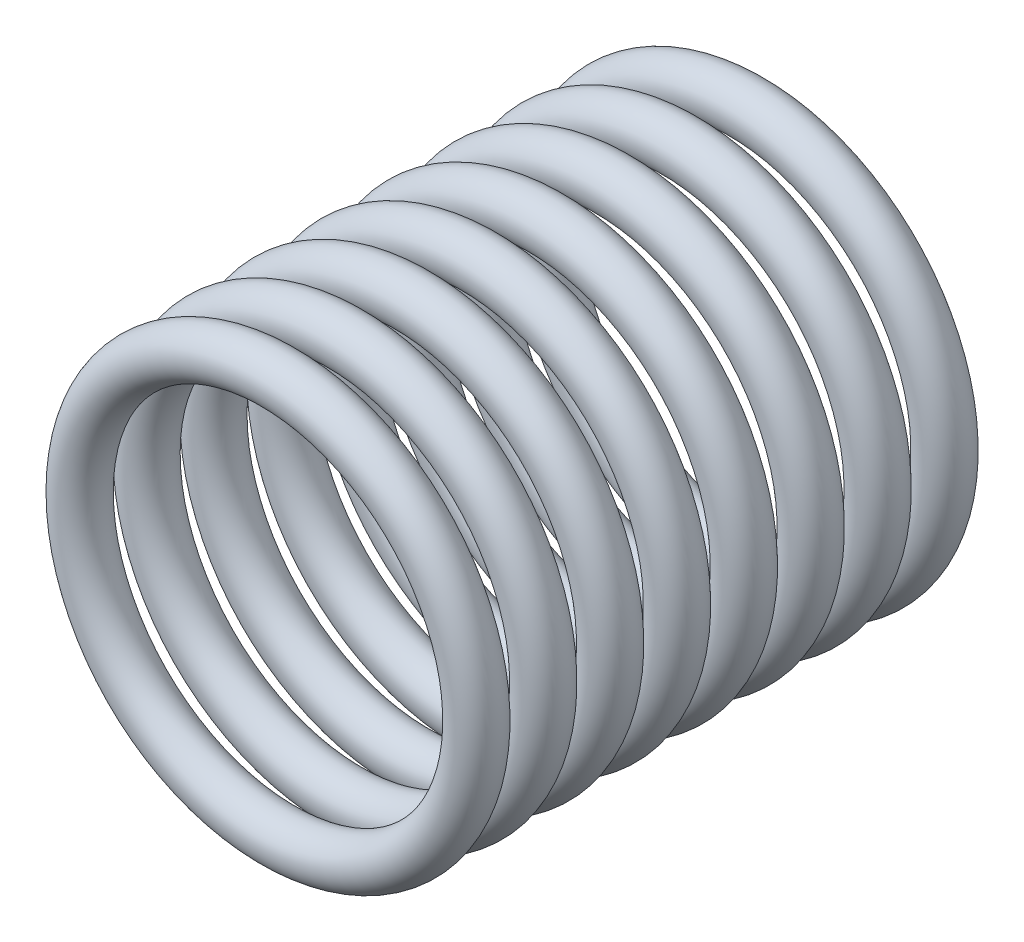
SolidWorks part; units mm, degrees
ref_plane "前视基准面" through (0, 0, 0) normal (0, 0, 1) x (1, 0, 0)
ref_plane "上视基准面" through (0, 0, 0) normal (0, 1, 0) x (1, 0, 0)
ref_plane "右视基准面" through (0, 0, 0) normal (1, 0, 0) x (0, 0, -1)
other "Configuration Table"
sketch "草图1" plane through (0, 0, 0) normal (0, 1, 0) x (1, 0, 0)
  line L0 (0, 0) -> (0, -13) construction
  circle A0 centre (5, -0.6) radius 0.6
  circle A1 centre (5, -2.2857) radius 0.6
  circle A2 centre (5, -3.9714) radius 0.6
  circle A3 centre (5, -5.6571) radius 0.6
  circle A4 centre (5, -7.3429) radius 0.6
  circle A5 centre (5, -9.0286) radius 0.6
  circle A6 centre (5, -10.7143) radius 0.6
  circle A7 centre (5, -12.4) radius 0.6
revolve "旋转1" add sketch "草图1" angle 360 about L0
